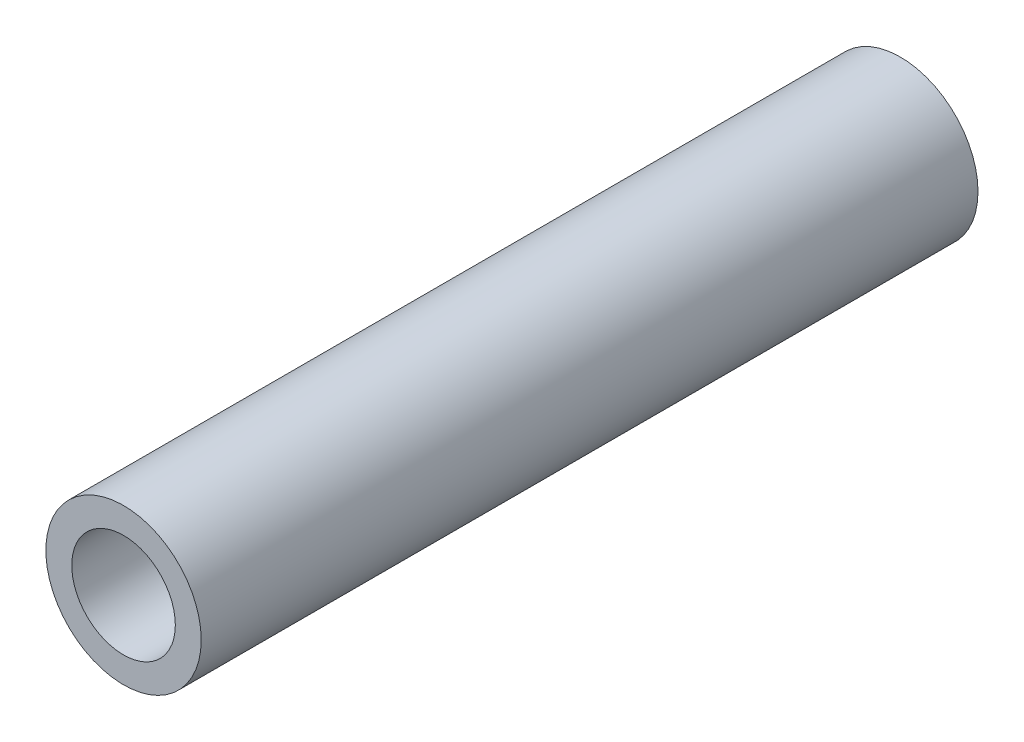
SolidWorks part; units mm, degrees
ref_plane "Front Plane" through (0, 0, 0) normal (0, 0, 1) x (1, 0, 0)
ref_plane "Top Plane" through (0, 0, 0) normal (0, 1, 0) x (1, 0, 0)
ref_plane "Right Plane" through (0, 0, 0) normal (1, 0, 0) x (0, 0, -1)
sketch "Sketch1" plane through (0, 0, 0) normal (0, 0, 1) x (1, 0, 0)
  circle A0 centre (0, 0) radius 3
  circle A1 centre (0, 0) radius 2
  dimension "D1" = 6
  dimension "D2" = 4
extrude "Boss-Extrude1" add sketch "Sketch1" along normal blind 30
